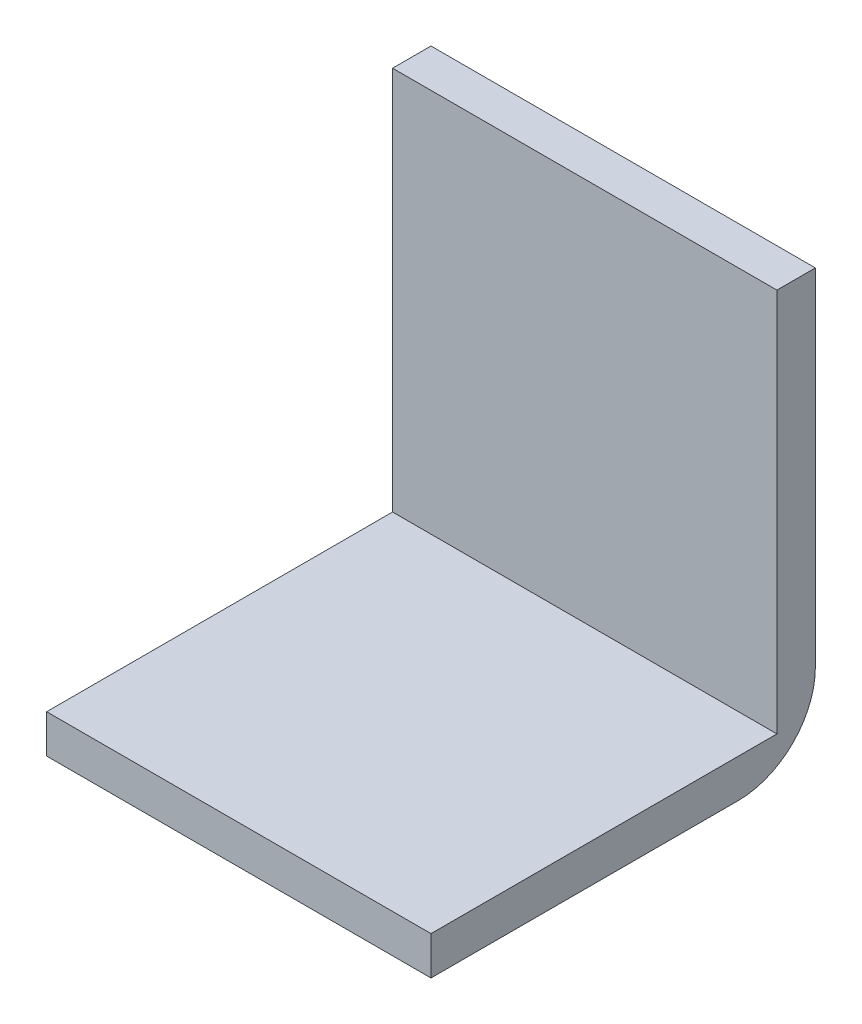
SolidWorks part; units mm, degrees
material "ABS"
ref_plane "Front Plane" through (0, 0, 0) normal (0, 0, 1) x (1, 0, 0)
ref_plane "Top Plane" through (0, 0, 0) normal (0, 1, 0) x (1, 0, 0)
ref_plane "Right Plane" through (0, 0, 0) normal (1, 0, 0) x (0, 0, -1)
sketch "Sketch1" plane through (0, 0, 0) normal (0, 0, 1) x (1, 0, 0)
  line L1 (-15.414, 27.8981) -> (34.586, 27.8981)
  line L2 (-15.414, 27.8981) -> (-15.414, -27.1019)
  line L3 (-15.414, -27.1019) -> (34.586, -27.1019)
  line L4 (34.586, 27.8981) -> (34.586, -27.1019)
  dimension "D1" = 55
  dimension "D2" = 50
extrude "Boss-Extrude1" add sketch "Sketch1" along normal blind 50
sketch "Sketch2" plane through (0, 0, 50) normal (0, 0, 1) x (1, 0, 0)
  line L0 (34.586, -27.1019) -> (34.586, 27.8981) construction
  line L1 (-15.414, 27.8981) -> (34.586, 27.8981)
  line L2 (-15.414, 27.8981) -> (-15.414, -22.1019)
  line L3 (-15.414, -22.1019) -> (34.586, -22.1019)
  line L4 (34.586, 27.8981) -> (34.586, -22.1019)
  dimension "D1" = 50
extrude "Cut-Extrude1" cut sketch "Sketch2" against normal blind 45
fillet "Fillet2" radius 10 1 edges at (9.586, -27.1019, 0)
